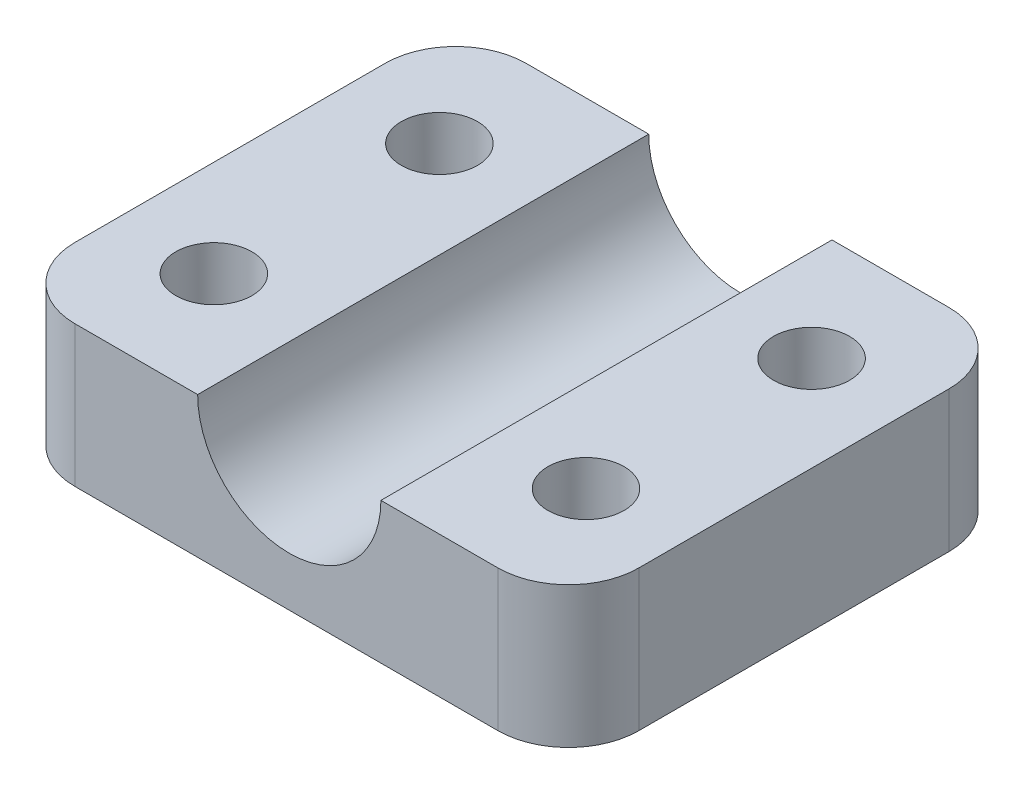
SolidWorks part; units mm, degrees
ref_plane "Front Plane" through (0, 0, 0) normal (0, 0, 1) x (1, 0, 0)
ref_plane "Top Plane" through (0, 0, 0) normal (0, 1, 0) x (1, 0, 0)
ref_plane "Right Plane" through (0, 0, 0) normal (1, 0, 0) x (0, 0, -1)
sketch "Sketch1" plane through (0, 0, 0) normal (0, 1, 0) x (1, 0, 0)
  line L1 (0, 0) -> (50.8, 0)
  line L2 (0, 0) -> (0, 40.64)
  line L3 (0, 40.64) -> (50.8, 40.64)
  line L4 (50.8, 0) -> (50.8, 40.64)
  dimension "D1" = 40.64
  dimension "D2" = 50.8
extrude "Boss-Extrude1" add sketch "Sketch1" along normal blind 12.7
sketch "Sketch2" plane through (0, 0, 0) normal (0, 0, 1) x (1, 0, 0)
  line L0 (25.4, 12.7) -> (25.4, 0) construction
  line L1 (0, 12.7) -> (50.8, 12.7) construction
  line L2 (0, 0) -> (50.8, 0) construction
  line L3 (0, 12.7) -> (0, 0) construction
  line L4 (17.399, 12.7) -> (33.909, 12.7)
  line L5 (17.399, 12.7) -> (33.909, 12.7)
  arc A2 (17.399, 12.7) -> (33.909, 12.7) centre (25.654, 12.7) ccw
  line M8 (50.8, 12.7) -> (0, 12.7)
  dimension "D1" = 25.4
  dimension "D2" = 16.51
extrude "Cut-Extrude1" cut sketch "Sketch2" against normal through all both and the other way through all contours L0 L5 A2 | L0 A2 M8
sketch "Sketch3" plane through (0, 12.7, 0) normal (0, 1, 0) x (1, 0, 0)
  line L0 (0, 20.32) -> (50.8, 20.32) construction
  line L1 (0, 40.64) -> (0, 0) construction
  line L2 (50.8, 0) -> (50.8, 40.64) construction
  line L6 (8.6995, 0) -> (8.6995, 40.64) construction
  line L7 (0, 0) -> (17.399, 0) construction
  line L8 (17.399, 40.64) -> (0, 40.64) construction
  line L9 (42.3545, 0) -> (42.3545, 40.64) construction
  line L10 (33.909, 0) -> (50.8, 0) construction
  line L11 (50.8, 40.64) -> (33.909, 40.64) construction
  line L12 (0, 10.16) -> (50.8, 10.16) construction
  line L13 (0, 30.48) -> (50.8, 30.48) construction
  circle A0 centre (8.6995, 10.16) radius 3.429
  circle A1 centre (42.2275, 10.16) radius 3.429
  circle A2 centre (42.2275, 30.48) radius 3.429
  circle A3 centre (8.6995, 30.48) radius 3.429
  dimension "D3" = 6.858
  dimension "D1" = 10.16
  dimension "D2" = 10.16
  dimension "D4" = 2
  dimension "D5" = 2
extrude "Cut-Extrude2" cut sketch "Sketch3" against normal through all both and the other way through all
fillet "Fillet1" radius 6.35 4 edges at (50.8, 6.35, 0) (0, 6.35, 0) (0, 6.35, -40.64) (50.8, 6.35, -40.64)
